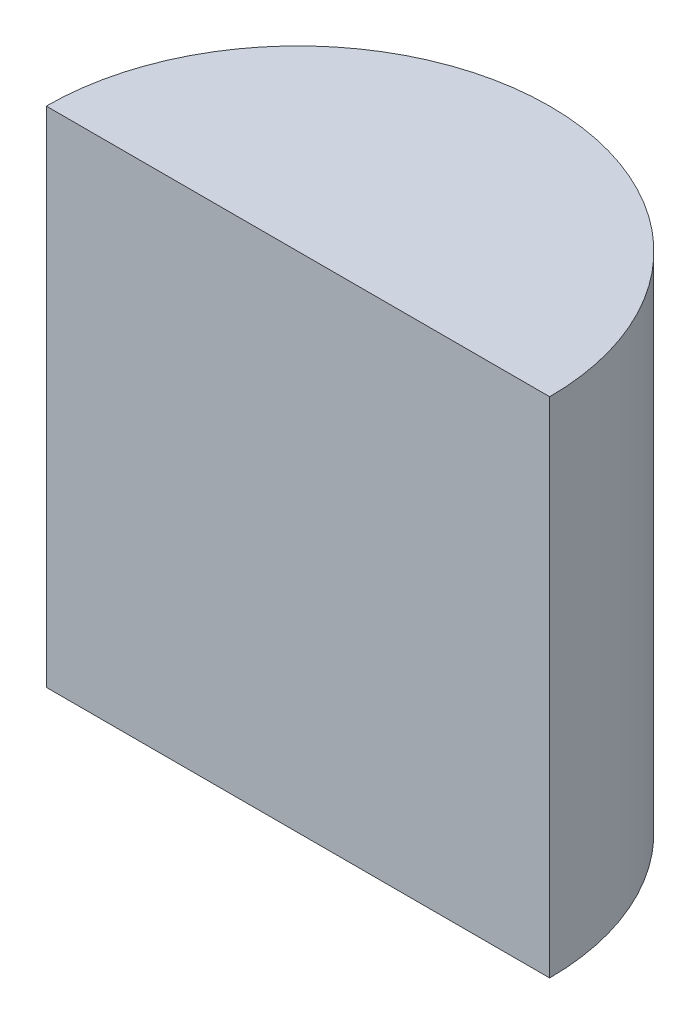
SolidWorks part; units mm, degrees
ref_plane "Front Plane" through (0, 0, 0) normal (0, 0, 1) x (1, 0, 0)
ref_plane "Top Plane" through (0, 0, 0) normal (0, 1, 0) x (1, 0, 0)
ref_plane "Right Plane" through (0, 0, 0) normal (1, 0, 0) x (0, 0, -1)
sketch "Sketch1" plane through (0, 0, 0) normal (0, 1, 0) x (1, 0, 0)
  line L0 (-5, 0) -> (5, 0)
  arc A0 (5, 0) -> (-5, 0) centre (0, 0) ccw
extrude "Boss-Extrude1" add sketch "Sketch1" along normal blind 10
